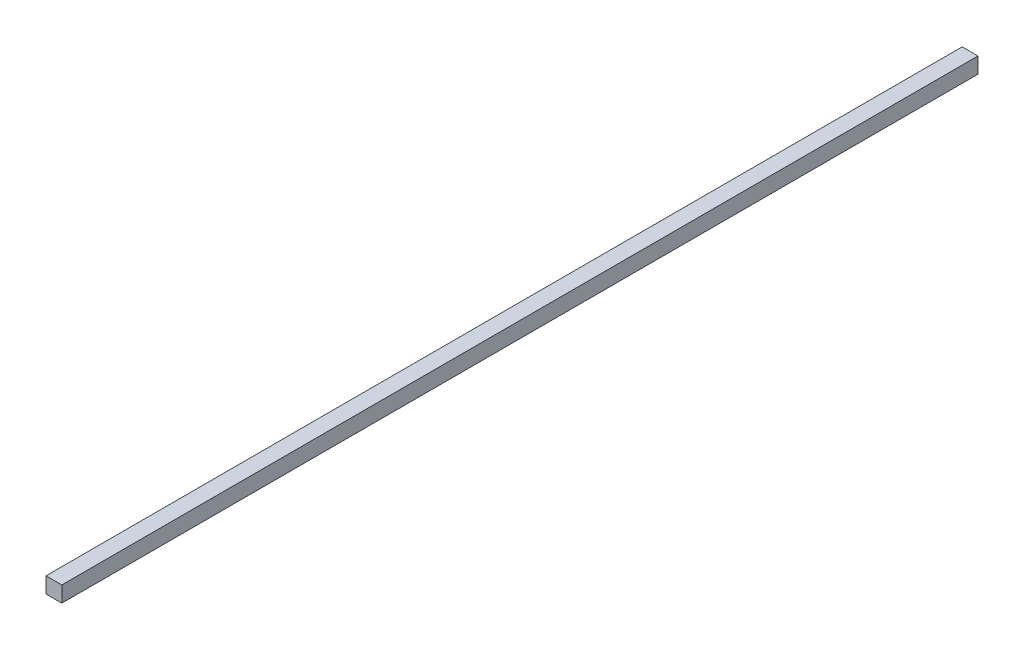
SolidWorks part; units mm, degrees
ref_plane "Front Plane" through (0, 0, 0) normal (0, 0, 1) x (1, 0, 0)
ref_plane "Top Plane" through (0, 0, 0) normal (0, 1, 0) x (1, 0, 0)
ref_plane "Right Plane" through (0, 0, 0) normal (1, 0, 0) x (0, 0, -1)
sketch "Sketch1" plane through (0, 0, 0) normal (0, 0, 1) x (1, 0, 0)
  line L1 (-20, -20) -> (20, -20)
  line L2 (-20, -20) -> (-20, 20)
  line L3 (-20, 20) -> (20, 20)
  line L4 (20, -20) -> (20, 20)
  line L5 (-20, -20) -> (20, 20) construction
  line L6 (-20, 20) -> (20, -20) construction
  point P0 (0, 0)
  dimension "D1" = 40
extrude "Boss-Extrude1" add sketch "Sketch1" along normal blind 2320
ref_plane "Plane1" through (0, 0, 1160) normal (0, 0, -1) x (-1, 0, 0)
